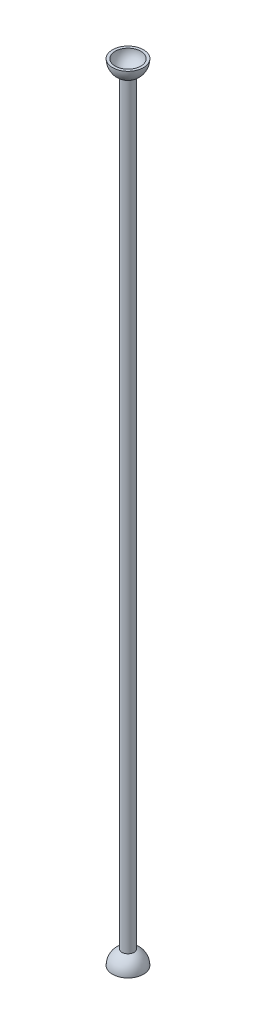
SolidWorks part; units mm, degrees
ref_plane "Front Plane" through (0, 0, 0) normal (0, 0, 1) x (1, 0, 0)
ref_plane "Top Plane" through (0, 0, 0) normal (0, 1, 0) x (1, 0, 0)
ref_plane "Right Plane" through (0, 0, 0) normal (1, 0, 0) x (0, 0, -1)
sketch "Sketch1" plane through (0, 0, 0) normal (0, 1, 0) x (1, 0, 0)
  circle A0 centre (0, 0) radius 2
extrude "Boss-Extrude1" add sketch "Sketch1" along normal blind 250 contours A0
sketch "Sketch2" plane through (0, 0, 0) normal (0, 0, 1) x (1, 0, 0)
  line L0 (0, 250) -> (2, 250) construction
  line L2 (2, 250) -> (-2, 250) construction
  line L3 (2, 0) -> (2, 250) construction
  line L4 (4.25, 254.7141) -> (5.1208, 254.7141)
  line L5 (0, 250.4641) -> (0, 249.5933)
  arc A3 (0, 250.4641) -> (4.25, 254.7141) centre (0, 254.7141) ccw
  arc A4 (0, 249.5933) -> (5.1208, 254.7141) centre (0, 254.7141) ccw
revolve "Revolve1" add sketch "Sketch2" angle 360 about L5
ref_plane "Plane1" through (0, 125, 0) normal (0, -1, 0) x (-1, 0, 0)
mirror "Mirror1" about plane through (0, 125, 0) normal (0, -1, 0) of "Revolve1"
